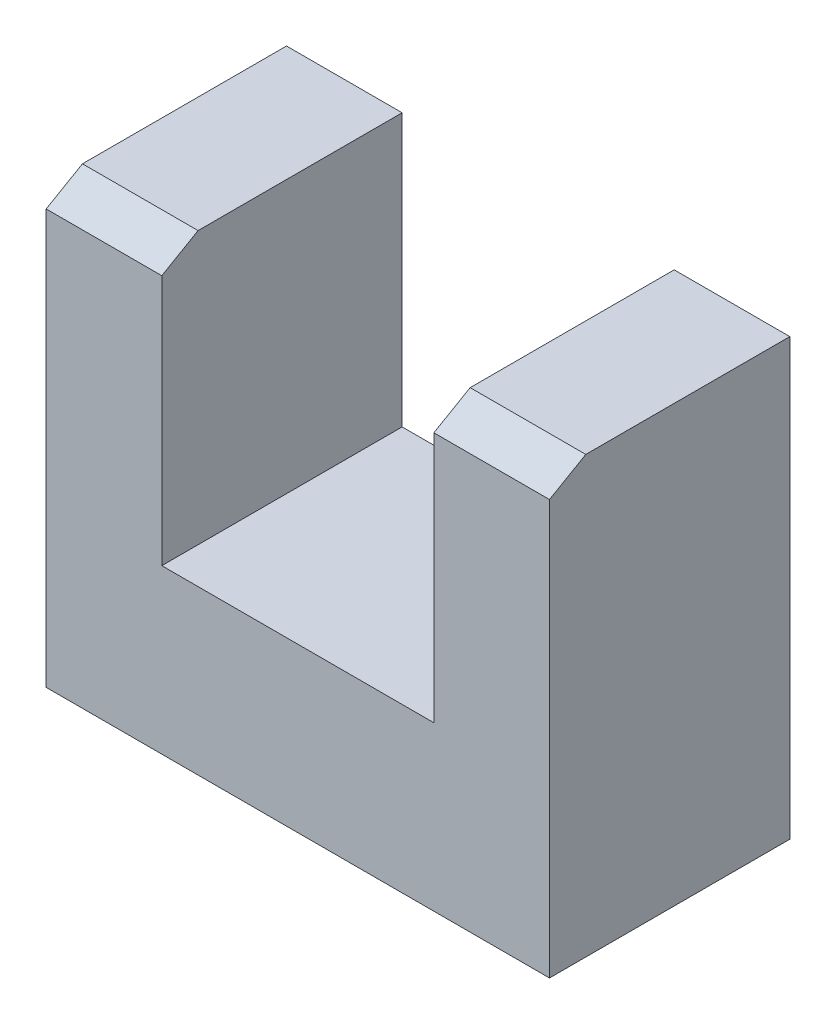
SolidWorks part; units mm, degrees
ref_plane "Front Plane" through (0, 0, 0) normal (0, 0, 1) x (1, 0, 0)
ref_plane "Top Plane" through (0, 0, 0) normal (0, 1, 0) x (1, 0, 0)
ref_plane "Right Plane" through (0, 0, 0) normal (1, 0, 0) x (0, 0, -1)
sketch "Sketch1" plane through (0, 0, 0) normal (0, 0, 1) x (1, 0, 0)
  line L0 (-1.5, 0) -> (1.5, 0)
  line L1 (1.5, 0) -> (1.5, 3)
  line L2 (1.5, 3) -> (2.775, 3)
  line L3 (2.775, 3) -> (2.775, -1.8)
  line L4 (2.775, -1.8) -> (-2.775, -1.8)
  line L5 (0, 0) -> (0, -1.8) construction
  line L6 (-2.775, 3) -> (-2.775, -1.8)
  line L7 (-1.5, 3) -> (-2.775, 3)
  line L8 (-1.5, 0) -> (-1.5, 3)
  dimension "D1" = 5.55
  dimension "D2" = 3
  dimension "D3" = 4.8
  dimension "D4" = 3
extrude "Boss-Extrude1" add sketch "Sketch1" along normal blind 2.65
chamfer "Chamfer1" distance 0.4 angle 30 2 edges at (2.1375, 3, 2.65) (-2.1375, 3, 2.65)
